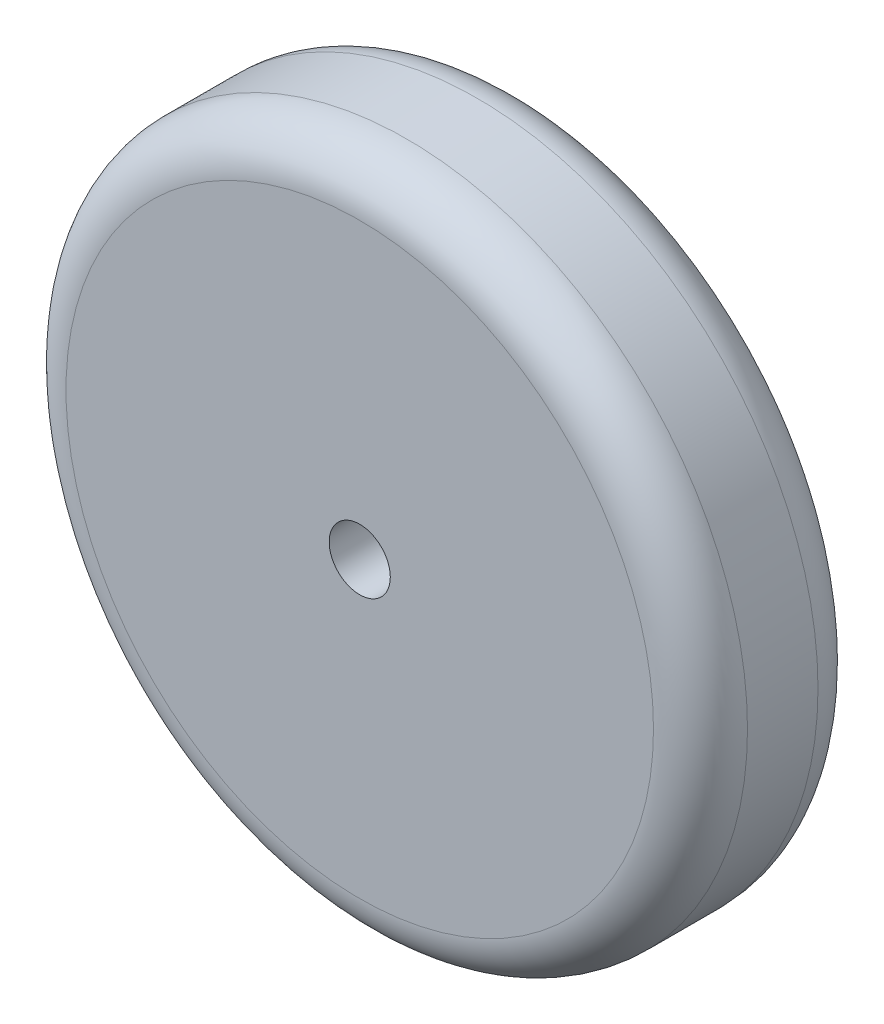
SolidWorks part; units mm, degrees
ref_plane "Front Plane" through (0, 0, 0) normal (0, 0, 1) x (1, 0, 0)
ref_plane "Top Plane" through (0, 0, 0) normal (0, 1, 0) x (1, 0, 0)
ref_plane "Right Plane" through (0, 0, 0) normal (1, 0, 0) x (0, 0, -1)
sketch "Sketch1" plane through (0, 0, 0) normal (0, 0, 1) x (1, 0, 0)
  circle A0 centre (0, 0) radius 72.5
  circle A1 centre (0, 0) radius 6.5
  dimension "D1" = 145
  dimension "D2" = 13
extrude "Boss-Extrude1" add sketch "Sketch1" along normal blind 35
fillet "Fillet1" radius 10 1 edges at (72.5, 0, 0)
fillet "Fillet2" radius 10 1 edges at (72.5, 0, 35)
